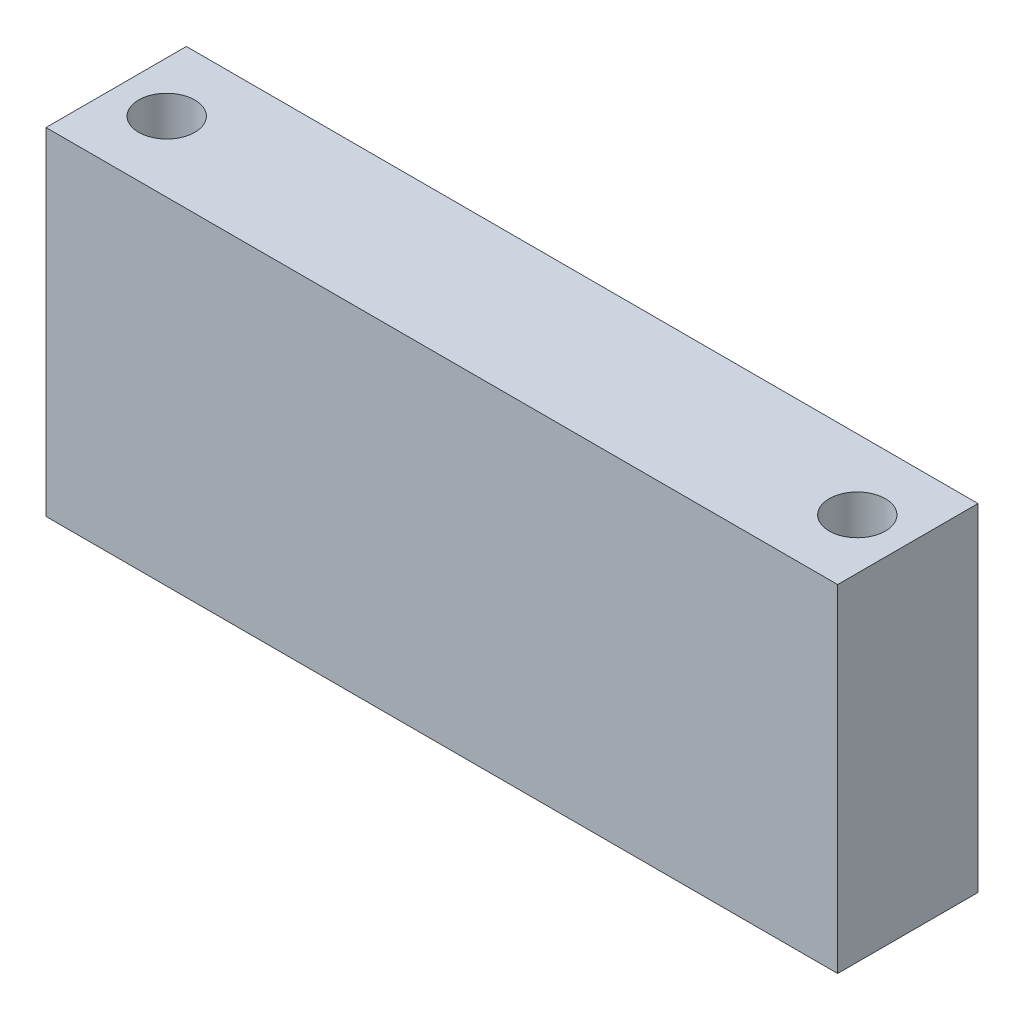
SolidWorks part; units mm, degrees
ref_plane "Front Plane" through (0, 0, 0) normal (0, 0, 1) x (1, 0, 0)
ref_plane "Top Plane" through (0, 0, 0) normal (0, 1, 0) x (1, 0, 0)
ref_plane "Right Plane" through (0, 0, 0) normal (1, 0, 0) x (0, 0, -1)
sketch "Sketch2" plane through (0, 0, 0) normal (0, 1, 0) x (1, 0, 0)
  line L1 (0, 0) -> (35.814, 0)
  line L2 (0, 0) -> (0, 6.35)
  line L3 (0, 6.35) -> (35.814, 6.35)
  line L4 (35.814, 0) -> (35.814, 6.35)
  dimension "D1" = 6.35
  dimension "D2" = 35.814
extrude "Boss-Extrude1" add sketch "Sketch2" along normal blind 15.24
sketch "Sketch3" plane through (0, 0, 0) normal (0, -1, 0) x (1, 0, 0)
  line L0 (0, -6.35) -> (0, 0) construction
  line L1 (35.814, 0) -> (35.814, -6.35) construction
  circle A0 centre (2.286, -3.175) radius 1.27
  circle A1 centre (33.528, -3.175) radius 1.27
  point P10 (35.814, -3.175)
  dimension "D1" = 2.54
  dimension "D3" = 2.286
  dimension "D2" = 2.286
extrude "Cut-Extrude1" cut sketch "Sketch3" against normal through all
